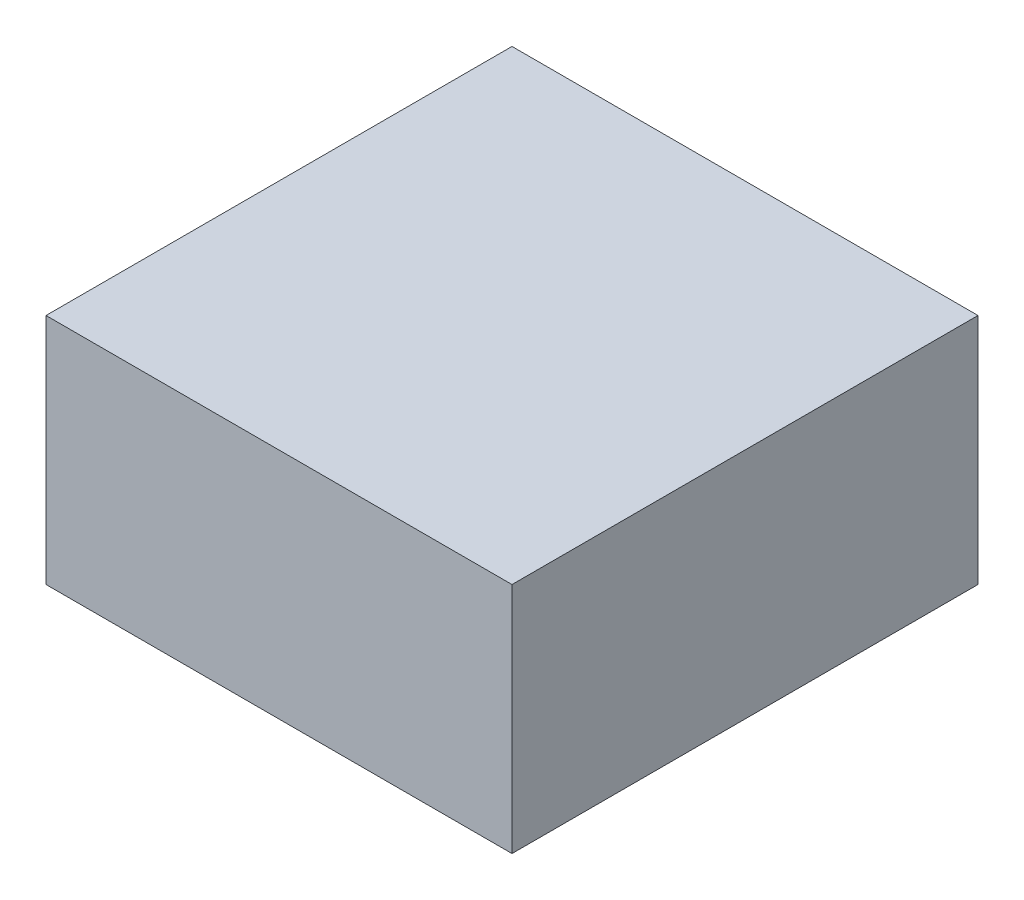
SolidWorks part; units mm, degrees
ref_plane "Front Plane" through (0, 0, 0) normal (0, 0, 1) x (1, 0, 0)
ref_plane "Top Plane" through (0, 0, 0) normal (0, 1, 0) x (1, 0, 0)
ref_plane "Right Plane" through (0, 0, 0) normal (1, 0, 0) x (0, 0, -1)
sketch "Sketch1" plane through (0, 0, 0) normal (0, 0, 1) x (1, 0, 0)
  line L1 (0, 0) -> (3.048, 0)
  line L2 (0, 0) -> (0, 1.524)
  line L3 (0, 1.524) -> (3.048, 1.524)
  line L4 (3.048, 0) -> (3.048, 1.524)
  dimension "D1" = 3.048
  dimension "D2" = 1.524
extrude "Boss-Extrude1" add sketch "Sketch1" along normal blind 3.048
